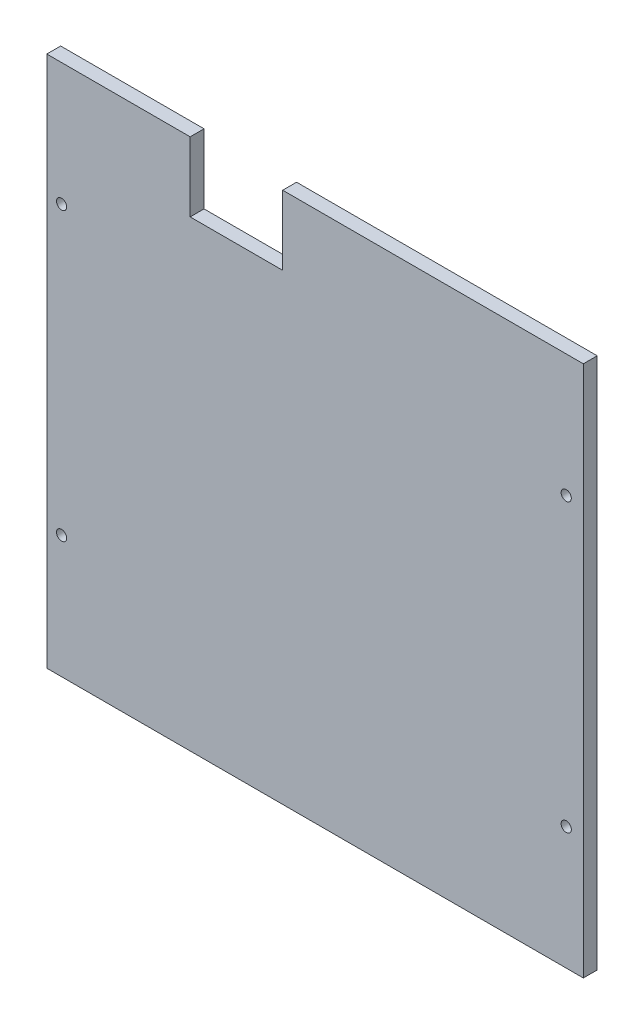
SolidWorks part; units mm, degrees
ref_plane "Front Plane" through (0, 0, 0) normal (0, 0, 1) x (1, 0, 0)
ref_plane "Top Plane" through (0, 0, 0) normal (0, 1, 0) x (1, 0, 0)
ref_plane "Right Plane" through (0, 0, 0) normal (1, 0, 0) x (0, 0, -1)
ref_plane "Plane1" through (0, 0, 6) normal (0, 0, 1) x (1, 0, 0)
sketch "Sketch1" plane through (0, 0, 6) normal (0, 0, 1) x (1, 0, 0)
  line L0 (-54, 85) -> (-54, 115)
  line L1 (-54, 115) -> (-116, 115)
  line L2 (-116, 115) -> (-116, -115)
  line L3 (-116, -115) -> (116, -115)
  line L4 (116, -115) -> (116, 115)
  line L5 (116, 115) -> (-14, 115)
  line L6 (-14, 115) -> (-14, 85)
  line L7 (-14, 85) -> (-54, 85)
  circle A0 centre (-109.6, 62) radius 2.2
  circle A1 centre (108.6, -62) radius 2.2
  circle A2 centre (108.6, 62) radius 2.2
  circle A3 centre (-109.6, -62) radius 2.2
extrude "Boss-Extrude1" add sketch "Sketch1" against normal blind 6
